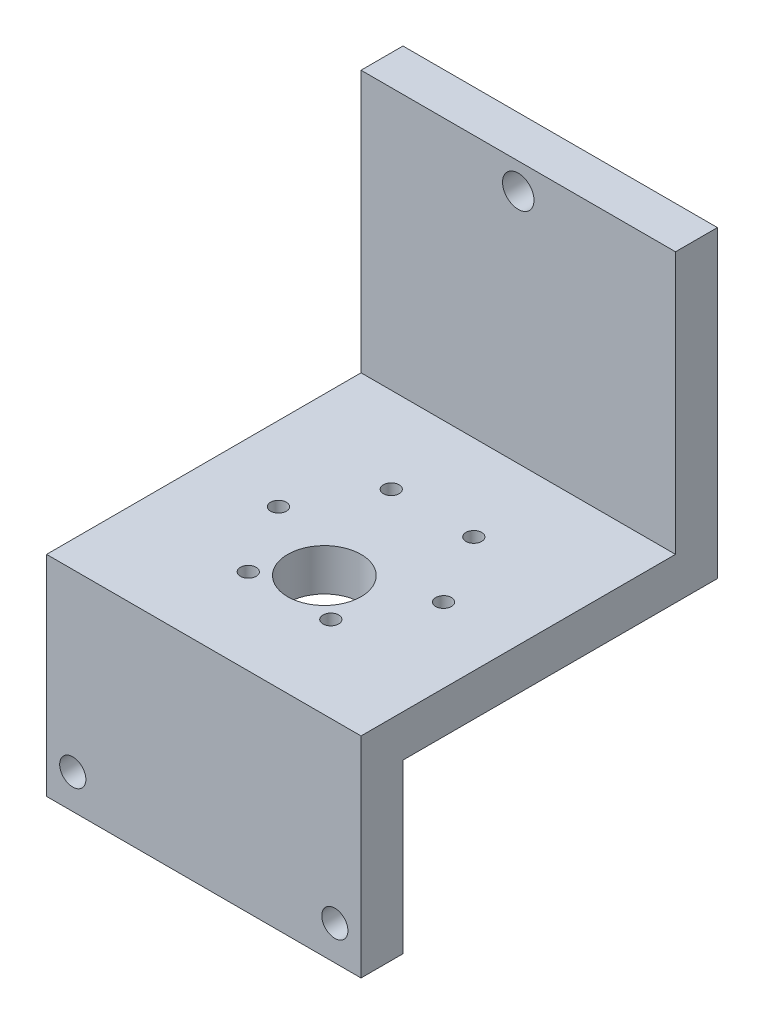
SolidWorks part; units mm, degrees
ref_plane "Front Plane" through (0, 0, 0) normal (0, 0, 1) x (1, 0, 0)
ref_plane "Top Plane" through (0, 0, 0) normal (0, 1, 0) x (1, 0, 0)
ref_plane "Right Plane" through (0, 0, 0) normal (1, 0, 0) x (0, 0, -1)
sketch "Sketch1" plane through (0, 0, 0) normal (1, 0, 0) x (0, 0, -1)
  line L1 (0, 50) -> (0, 0)
  line L2 (0, 0) -> (-52, 0)
  line L3 (-52, 0) -> (-52, -8)
  line L4 (-52, -8) -> (8, -8)
  line L5 (8, -8) -> (8, 50)
  line L6 (8, 50) -> (0, 50)
  dimension "D1" = 52
  dimension "D2" = 8
  dimension "D3" = 8
  dimension "D4" = 50
extrude "Boss-Extrude1" add sketch "Sketch1" along normal mid plane 60
sketch "Sketch2" plane through (0, 0, 0) normal (0, 1, 0) x (1, 0, 0)
  circle A0 centre (0, -37) radius 7
  circle A1 centre (15.75, -30) radius 1.5
  circle A2 centre (7.875, -43.6399) radius 1.5
  circle A3 centre (-7.875, -43.6399) radius 1.5
  circle A4 centre (-15.75, -30) radius 1.5
  circle A5 centre (-7.875, -16.3601) radius 1.5
  circle A6 centre (7.875, -16.3601) radius 1.5
  point P5 (0, -30)
  point P19 (0, -30)
  dimension "D2" = 14
  dimension "D5" = 3
  dimension "D1" = 37
  dimension "D3" = 7
  dimension "D4" = 15.75
  dimension "D6" = 6
extrude "Cut-Extrude1" cut sketch "Sketch2" against normal blind 55
sketch "Sketch3" plane through (0, 0, 0) normal (0, 0, 1) x (1, 0, 0)
  circle A0 centre (0, 45) radius 3
  dimension "D1" = 6
  dimension "D2" = 45
extrude "Cut-Extrude2" cut sketch "Sketch3" against normal blind 55
sketch "Sketch4" plane through (30, 0, 0) normal (1, 0, 0) x (0, 0, -1)
  line L1 (-52, 0) -> (-60, 0)
  line L2 (-52, 0) -> (-52, -40)
  line L3 (-52, -40) -> (-60, -40)
  line L4 (-60, 0) -> (-60, -40)
  dimension "D1" = 8
  dimension "D2" = 40
extrude "Boss-Extrude2" add sketch "Sketch4" against normal up to vertex (60 mm away)
sketch "Sketch5" plane through (0, 0, 60) normal (0, 0, 1) x (1, 0, 0)
  circle A0 centre (25, -33.45) radius 2.5 construction
  circle A1 centre (-25, -33.45) radius 2.5 construction
  circle A2 centre (25, -33.45) radius 2.5
  circle A3 centre (-25, -33.45) radius 2.5
extrude "Cut-Extrude3" cut sketch "Sketch5" against normal blind 10
